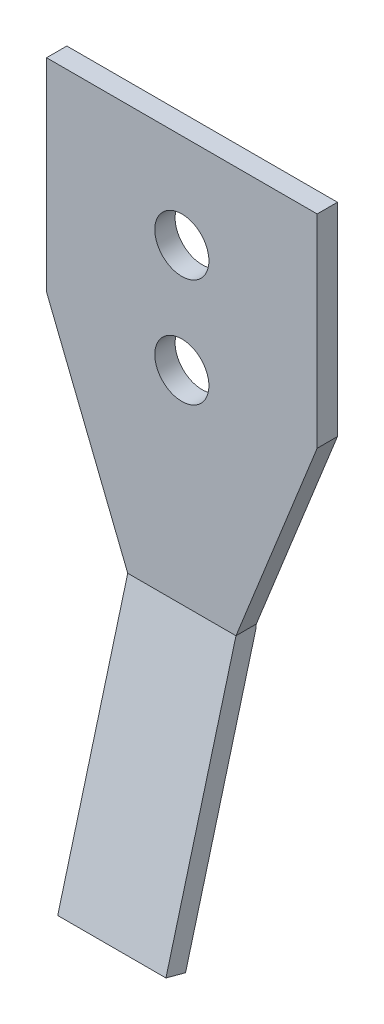
SolidWorks part; units mm, degrees
material "Mahogany"
ref_plane "Front Plane" through (0, 0, 0) normal (0, 0, 1) x (1, 0, 0)
ref_plane "Top Plane" through (0, 0, 0) normal (0, 1, 0) x (1, 0, 0)
ref_plane "Right Plane" through (0, 0, 0) normal (1, 0, 0) x (0, 0, -1)
sketch "Sketch1" plane through (0, 0, 0) normal (0, 0, 1) x (1, 0, 0)
  line L1 (0, 0) -> (-200, 0)
  line L2 (0, 0) -> (0, 300)
  line L3 (0, 300) -> (-200, 300)
  line L4 (-200, 0) -> (-200, 300)
  circle A0 centre (-100, 230) radius 20
  circle A1 centre (-100, 150) radius 20
  dimension "D3" = 40
  dimension "D4" = 40
  dimension "D1" = 200
  dimension "D2" = 300
  dimension "D5" = 100
  dimension "D6" = 70
  dimension "D7" = 100
  dimension "D8" = 80
extrude "Boss-Extrude1" add sketch "Sketch1" along normal blind 15
sketch "Sketch2" plane through (0, 0, 0) normal (0, 0, -1) x (-1, 0, 0)
  line L0 (0, 0) -> (60, 0)
  line L1 (200, 0) -> (0, 0) construction
  line L2 (60, 0) -> (0, 150)
  line L3 (0, 0) -> (0, 300) construction
  line L4 (0, 150) -> (0, 0)
  line L5 (200, 0) -> (140, 0)
  line L6 (140, 0) -> (200, 150)
  line L7 (200, 300) -> (200, 0) construction
  line L8 (200, 150) -> (200, 0)
  dimension "D1" = 150
  dimension "D2" = 60
  dimension "D3" = 60
  dimension "D4" = 150
extrude "Cut-Extrude1" cut sketch "Sketch2" against normal blind 15
sketch "Sketch3" plane through (0, 0, 0) normal (0, -1, 0) x (1, 0, 0)
  line L1 (-60, 0) -> (-140, 0)
  line L2 (-60, 0) -> (-60, 15)
  line L3 (-60, 15) -> (-140, 15)
  line L4 (-140, 0) -> (-140, 15)
revolve "Revolve1" add sketch "Sketch3" angle 15 about L3
sketch "Sketch4" plane through (0, -3.75, 1.0048) normal (0, -0.9659, 0.2588) x (1, 0, 0)
  line L1 (-140, -0.5111) -> (-60, -0.5111)
  line L2 (-140, -0.5111) -> (-140, 14.4889)
  line L3 (-140, 14.4889) -> (-60, 14.4889)
  line L4 (-60, -0.5111) -> (-60, 14.4889)
extrude "Boss-Extrude3" add sketch "Sketch4" along normal blind 200
